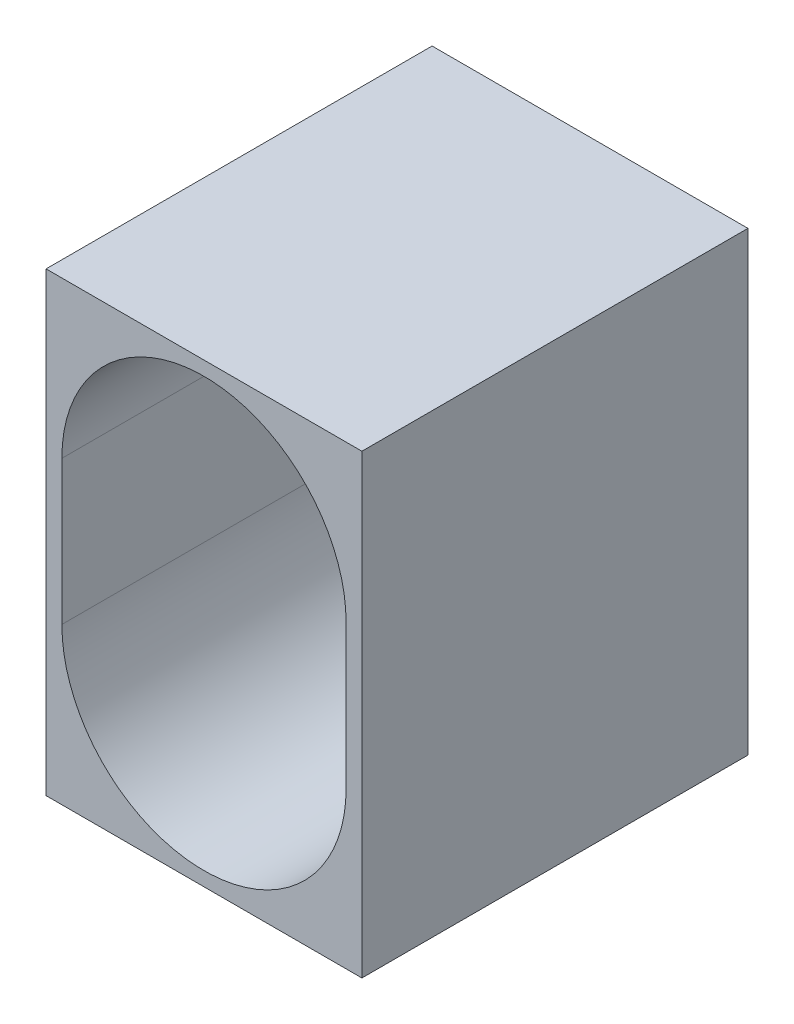
SolidWorks part; units mm, degrees
material "6061 Alloy"
ref_plane "Front Plane" through (0, 0, 0) normal (0, 0, 1) x (1, 0, 0)
ref_plane "Top Plane" through (0, 0, 0) normal (0, 1, 0) x (1, 0, 0)
ref_plane "Right Plane" through (0, 0, 0) normal (1, 0, 0) x (0, 0, -1)
sketch "Sketch4" plane through (0, 0, 0) normal (0, 0, 1) x (1, 0, 0)
  line L1 (-30.2849, 20.5607) -> (14.7151, 20.5607)
  line L2 (-30.2849, 20.5607) -> (-30.2849, -44.4393)
  line L3 (-30.2849, -44.4393) -> (14.7151, -44.4393)
  line L4 (14.7151, 20.5607) -> (14.7151, -44.4393)
  dimension "D1" = 45
  dimension "D2" = 65
extrude "Boss-Extrude2" add sketch "Sketch4" along normal blind 55
sketch "Sketch5" plane through (0, 0, 55) normal (0, 0, 1) x (1, 0, 0)
  line L0 (-7.7849, -22.1893) -> (-7.7849, -1.6893) construction
  line L1 (-21.0349, -22.1893) -> (-21.0349, -1.6893) construction
  line L2 (5.4651, -22.1893) -> (5.4651, -1.6893) construction
  line L3 (-30.2849, -44.4393) -> (14.7151, -44.4393) construction
  line L4 (-30.2849, 20.5607) -> (-30.2849, -44.4393) construction
  line L5 (-28.0349, -22.1893) -> (-28.0349, -1.6893)
  line L6 (12.4651, -22.1893) -> (12.4651, -1.6893)
  arc A0 (-21.0349, -22.1893) -> (5.4651, -22.1893) centre (-7.7849, -22.1893) ccw construction
  arc A1 (5.4651, -1.6893) -> (-21.0349, -1.6893) centre (-7.7849, -1.6893) ccw construction
  arc A2 (12.4651, -1.6893) -> (-28.0349, -1.6893) centre (-7.7849, -1.6893) ccw
  arc A3 (-28.0349, -22.1893) -> (12.4651, -22.1893) centre (-7.7849, -22.1893) ccw
  point P2 (-7.7849, -11.9393)
  dimension "D3" = 7
  dimension "D1" = 32.5
  dimension "D2" = 22.5
extrude "Cut-Extrude1" cut sketch "Sketch5" against normal blind 52.5
hole_wizard "1/4-28 Tapped Hole1" positions "Sketch6" profile "Sketch7" tap size "1/4-28" standard "ANSI Inch" end condition up to next
sketch "Sketch6" plane through (0, 0, 0) normal (0, 0, -1) x (-1, 0, 0)
  line L0 (-14.7151, -44.4393) -> (-14.7151, 20.5607) construction
  line L1 (-14.7151, 20.5607) -> (30.2849, 20.5607) construction
  point P0 (7.7849, -16.4393)
  dimension "D1" = 22.5
  dimension "D2" = 37
sketch "Sketch7" plane through (-7.7849, -16.4393, 0) normal (1, 0, 0) x (0, 1, 0)
  line L0 (0, 0) -> (0, 2.5)
  line L1 (0, 2.5) -> (2.7051, 2.5)
  line L2 (2.7051, 2.5) -> (2.7051, 0)
  line L5 (2.7051, 0) -> (0, 0)
  line L11 (0, -6.35) -> (0, 107.95) construction
  dimension "Thru Tap Drill Dia." = 5.4102
  dimension "Thru Tap Drill Depth" = 2.5
cosmetic thread "Hole Thread1" parameters "D2"=6.35
hole_wizard "M2x0.4 Tapped Hole1" positions "Sketch14" profile "Sketch15" tap size "M2x0.4" standard "ANSI Metric"
sketch "Sketch14" plane through (0, 0, 0) normal (0, 0, -1) x (-1, 0, 0)
  line L0 (-14.7151, -44.4393) -> (-14.7151, 20.5607) construction
  line L1 (30.2849, -44.4393) -> (-14.7151, -44.4393) construction
  point P0 (-10.7151, -40.4393)
  dimension "D1" = 4
  dimension "D2" = 4
sketch "Sketch15" plane through (10.7151, -40.4393, 0) normal (1, 0, 0) x (0, 1, 0)
  line L0 (0, 0) -> (0, 8.4807)
  line L1 (0, 8.4807) -> (0.8, 8)
  line L2 (0.8, 8) -> (0.8, 0)
  line L5 (0.8, 0) -> (0, 0)
  line L10 (0, 8.4807) -> (-0.8, 8) construction
  line L11 (0, -6.35) -> (0, 107.95) construction
  dimension "Tap Drill Dia." = 1.6
  dimension "Tap Drill Depth" = 8
  dimension "Drill Angle" = 118
cosmetic thread "Hole Thread2" parameters "D1"=4, "D2"=2
hole_wizard "M2x0.4 Tapped Hole2" positions "3DSketch2" profile "Sketch19" tap size "M2x0.4" standard "ANSI Metric"
sketch3d "3DSketch2"
  line L0 (-30.2849, 20.5607, 0) -> (-30.2849, -44.4393, 0) construction
  line L1 (-30.2849, -44.4393, 0) -> (14.7151, -44.4393, 0) construction
  point P0 (-26.2849, -40.4393, 0)
  dimension "D1" = 4
  dimension "D2" = 4
sketch "Sketch19" plane through (-26.2849, -40.4393, 0) normal (1, 0, 0) x (0, 1, 0)
  line L0 (0, 0) -> (0, 8.4807)
  line L1 (0, 8.4807) -> (0.8, 8)
  line L2 (0.8, 8) -> (0.8, 0)
  line L5 (0.8, 0) -> (0, 0)
  line L10 (0, 8.4807) -> (-0.8, 8) construction
  line L11 (0, -6.35) -> (0, 107.95) construction
  dimension "Tap Drill Dia." = 1.6
  dimension "Tap Drill Depth" = 8
  dimension "Drill Angle" = 118
cosmetic thread "Hole Thread3" parameters "D1"=4, "D2"=2
